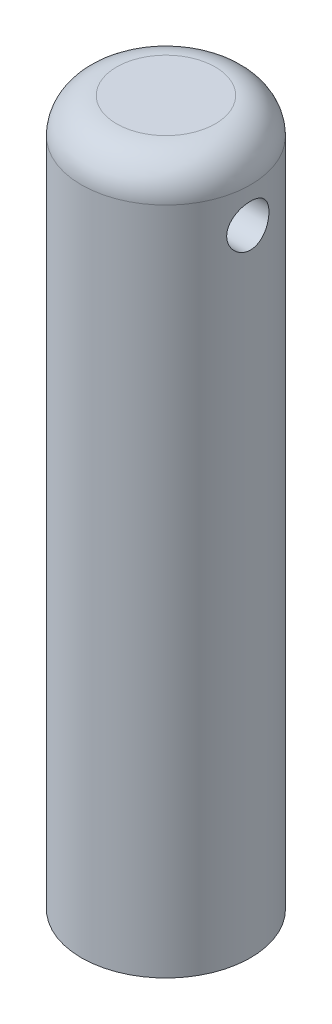
SolidWorks part; units mm, degrees
ref_plane "Спереди" through (0, 0, 0) normal (0, 0, 1) x (1, 0, 0)
ref_plane "Сверху" through (0, 0, 0) normal (0, 1, 0) x (1, 0, 0)
ref_plane "Справа" through (0, 0, 0) normal (1, 0, 0) x (0, 0, -1)
sketch "Эскиз1" plane through (0, 0, 0) normal (0, 1, 0) x (1, 0, 0)
  circle A0 centre (0, 0) radius 6
  circle A1 centre (0, 0) radius 12
  dimension "D1" = 12
  dimension "D2" = 24
extrude "Вытянуть1" add sketch "Эскиз1" along normal blind 80
sketch "Эскиз2" plane through (0, 0, 0) normal (0, -1, 0) x (1, 0, 0)
  line L1 (6.8836, -3.9335) -> (6.8483, 3.9947)
  line L2 (6.8483, 3.9947) -> (-0.0353, 7.9281)
  line L3 (-0.0353, 7.9281) -> (-6.8836, 3.9335)
  line L4 (-6.8836, 3.9335) -> (-6.8483, -3.9947)
  line L5 (-6.8483, -3.9947) -> (0.0353, -7.9281)
  line L6 (0.0353, -7.9281) -> (6.8836, -3.9335)
  circle A0 centre (0, 0) radius 6.866 construction
  circle A1 centre (0, 0) radius 6 construction
  dimension "D1" = 13.7321
  dimension "D2" = 6.8836
extrude "Вырез-Вытянуть1" cut sketch "Эскиз2" against normal blind 17
fillet "Скругление1" radius 1 6 edges at (-6.8483, 8.5, -3.9947) (0.0353, 8.5, -7.9281) (6.8836, 8.5, -3.9335) (6.8483, 8.5, 3.9947) (-0.0353, 8.5, 7.9281) (-6.8836, 8.5, 3.9335)
sketch "Эскиз3" plane through (0, 80, 0) normal (0, 1, 0) x (1, 0, 0)
  circle A0 centre (0, 0) radius 12
  dimension "D1" = 24
extrude "Вытянуть2" add sketch "Эскиз3" along normal blind 20
fillet "Скругление2" radius 5 1 edges at (0, 100, 12)
sketch "Эскиз4" plane through (0, 0, 0) normal (1, 0, 0) x (0, 0, -1)
  line L0 (0, 100) -> (0, 104.3693) construction
  circle A0 centre (0, 90) radius 3
  dimension "D1" = 6
  dimension "D2" = 90
extrude "Вытянуть3" cut sketch "Эскиз4" against normal mid plane 45
